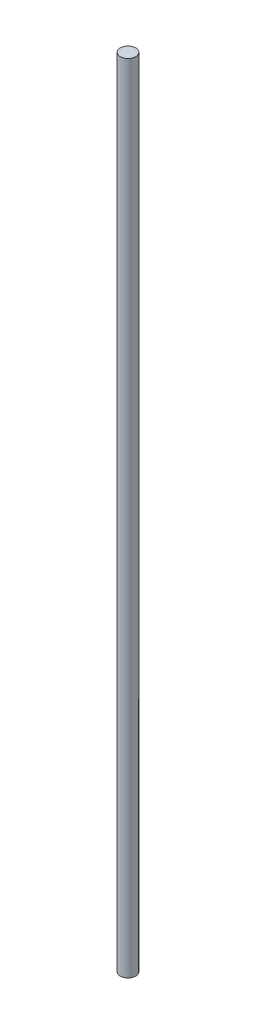
SolidWorks part; units mm, degrees
ref_plane "Front Plane" through (0, 0, 0) normal (0, 0, 1) x (1, 0, 0)
ref_plane "Top Plane" through (0, 0, 0) normal (0, 1, 0) x (1, 0, 0)
ref_plane "Right Plane" through (0, 0, 0) normal (1, 0, 0) x (0, 0, -1)
sketch "Sketch1" plane through (0, 0, 0) normal (0, 1, 0) x (1, 0, 0)
  circle A0 centre (0, 0) radius 6.35
extrude "Boss-Extrude1" add sketch "Sketch1" along normal blind 660.4
